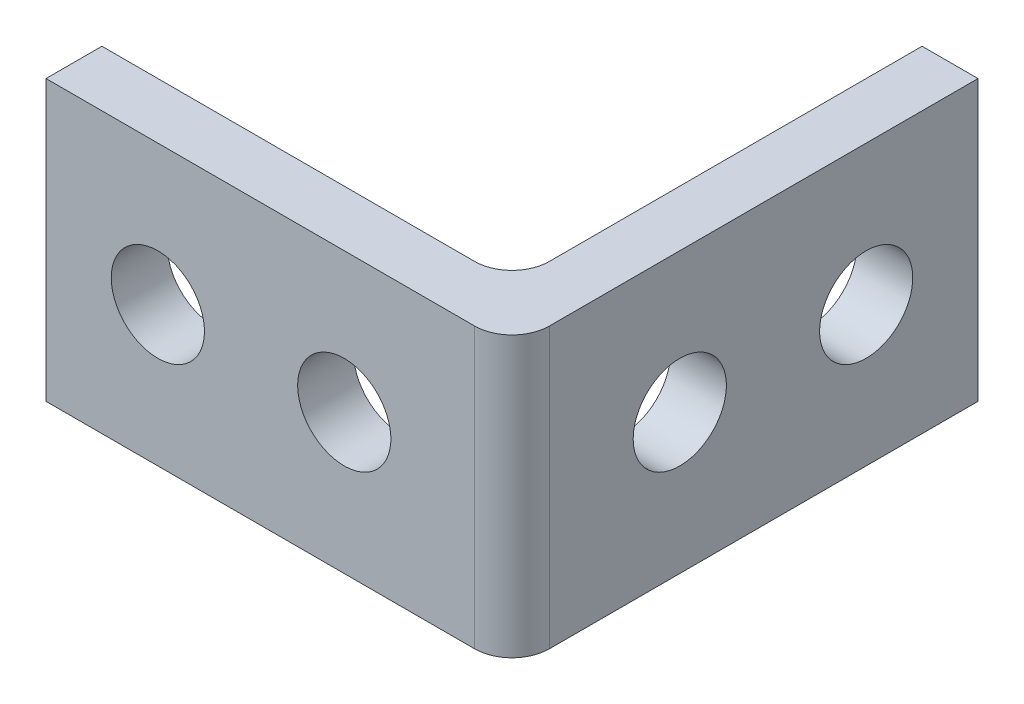
SolidWorks part; units mm, degrees
material "AISI 1045 Acero estirado en frío"
ref_plane "Front" through (0, 0, 0) normal (0, 0, 1) x (1, 0, 0)
ref_plane "Top" through (0, 0, 0) normal (0, 1, 0) x (1, 0, 0)
ref_plane "Right" through (0, 0, 0) normal (1, 0, 0) x (0, 0, -1)
sketch "Croquis1" plane through (0, 0, 0) normal (0, 1, 0) x (1, 0, 0)
  line L0 (0, 0) -> (23, 0)
  line L1 (25, 2) -> (25, 25)
  line L2 (25, 25) -> (22, 25)
  line L3 (22, 25) -> (22, 5)
  line L4 (20, 3) -> (0, 3)
  line L5 (0, 3) -> (0, 0)
  arc A0 (22, 5) -> (20, 3) centre (20, 5) cw
  arc A1 (23, 0) -> (25, 2) centre (23, 2) ccw
  point P11 (25, 0)
  dimension "D4" = 2
  dimension "D1" = 3
  dimension "D2" = 25
  dimension "D3" = 25
extrude "Saliente-Extruir1" add sketch "Croquis1" along normal blind 15
sketch "Croquis2" plane through (0, 0, -3) normal (0, 0, -1) x (-1, 0, 0)
  line L0 (0, 7.5) -> (-19.3673, 7.5) construction
  line L1 (0, 15) -> (0, 0) construction
  circle A0 centre (-16, 7.5) radius 2.5
  circle A1 centre (-6, 7.5) radius 2.5
  dimension "D1" = 5
  dimension "D2" = 10
  dimension "D3" = 9
extrude "Cortar-Extruir1" cut sketch "Croquis2" against normal blind 20
sketch "Croquis3" plane through (22, 0, 0) normal (-1, 0, 0) x (0, 0, 1)
  line L0 (-25, 7.5) -> (-19, 7.5) construction
  line L1 (-25, 15) -> (-25, 0) construction
  circle A0 centre (-9, 7.5) radius 2.5
  circle A1 centre (-19, 7.5) radius 2.5
  dimension "D1" = 5
  dimension "D2" = 9
  dimension "23" = 10
extrude "Cortar-Extruir2" cut sketch "Croquis3" against normal blind 15
